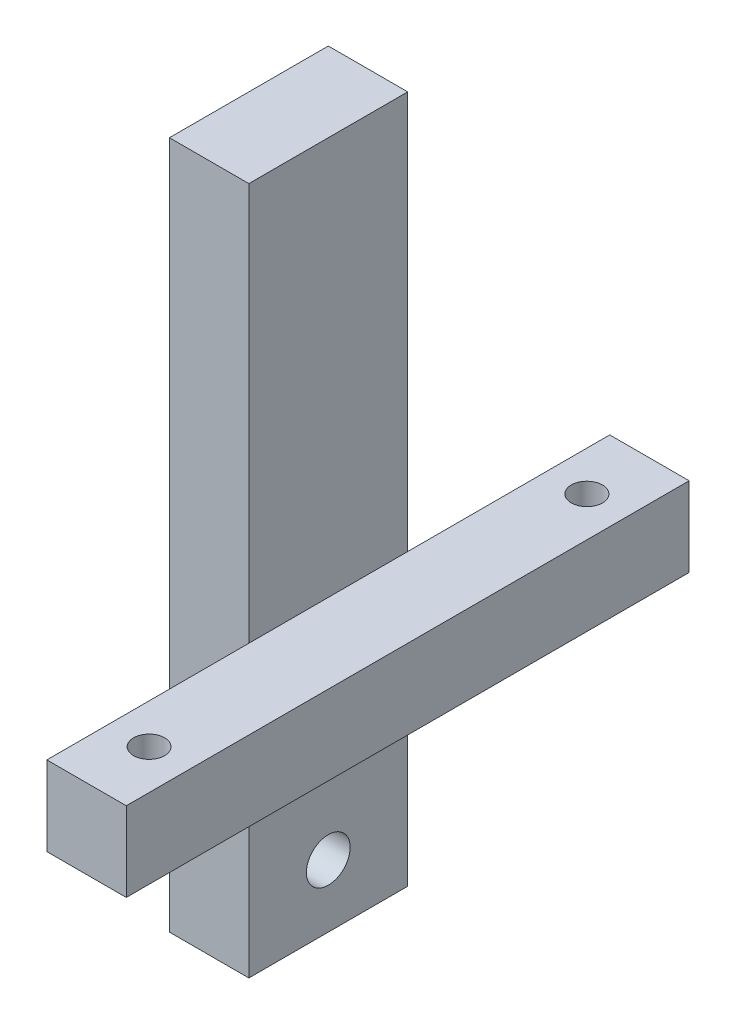
SolidWorks part; units mm, degrees
ref_plane "Alzado" through (0, 0, 0) normal (0, 0, 1) x (1, 0, 0)
ref_plane "Planta" through (0, 0, 0) normal (0, 1, 0) x (1, 0, 0)
ref_plane "Vista lateral" through (0, 0, 0) normal (1, 0, 0) x (0, 0, -1)
sketch "Croquis1" plane through (0, 0, 0) normal (0, 1, 0) x (1, 0, 0)
  line L1 (6.35, -12.7) -> (-6.35, -12.7)
  line L2 (6.35, -12.7) -> (6.35, 12.7)
  line L3 (6.35, 12.7) -> (-6.35, 12.7)
  line L4 (-6.35, -12.7) -> (-6.35, 12.7)
  line L5 (6.35, -12.7) -> (-6.35, 12.7) construction
  line L6 (6.35, 12.7) -> (-6.35, -12.7) construction
  point P0 (0, 0)
  dimension "D1" = 25.4
  dimension "D2" = 12.7
extrude "Saliente-Extruir1" add sketch "Croquis1" along normal blind 110
sketch "Croquis2" plane through (6.35, 0, 0) normal (1, 0, 0) x (0, 0, -1)
  line L0 (-12.7, 0) -> (12.7, 0) construction
  line L1 (-45, 46.35) -> (45, 46.35)
  line L2 (-45, 46.35) -> (-45, 33.65)
  line L3 (-45, 33.65) -> (45, 33.65)
  line L4 (45, 46.35) -> (45, 33.65)
  line L5 (-45, 46.35) -> (45, 33.65) construction
  line L6 (-45, 33.65) -> (45, 46.35) construction
  point P0 (0, 40)
  point P5 (0, 0)
  dimension "D1" = 12.7
  dimension "D2" = 90
  dimension "D3" = 40
extrude "Saliente-Extruir2" add sketch "Croquis2" along normal blind 12.7
sketch "Croquis3" plane through (6.35, 0, 0) normal (1, 0, 0) x (0, 0, -1)
  line L0 (-12.7, 0) -> (12.7, 0) construction
  circle A0 centre (0, 10) radius 3.5
  dimension "D2" = 7
  dimension "D1" = 10
extrude "Cortar-Extruir1" cut sketch "Croquis3" against normal through all
sketch "Croquis4" plane through (0, 46.35, 0) normal (0, 1, 0) x (1, 0, 0)
  line L0 (12.7, -45) -> (12.7, 45) construction
  line L1 (19.05, -45) -> (6.35, -45) construction
  line L2 (19.05, 45) -> (6.35, 45) construction
  circle A0 centre (12.7, 35) radius 2.4949
  circle A1 centre (12.7, -35) radius 2.4823
  point P12 (29.2199, -16.5345)
  dimension "D1" = 70
  dimension "D2" = 35
extrude "Cortar-Extruir2" cut sketch "Croquis4" against normal through all
equation "\"D2@Croquis4\"=\"D1@Croquis4\"/2"
